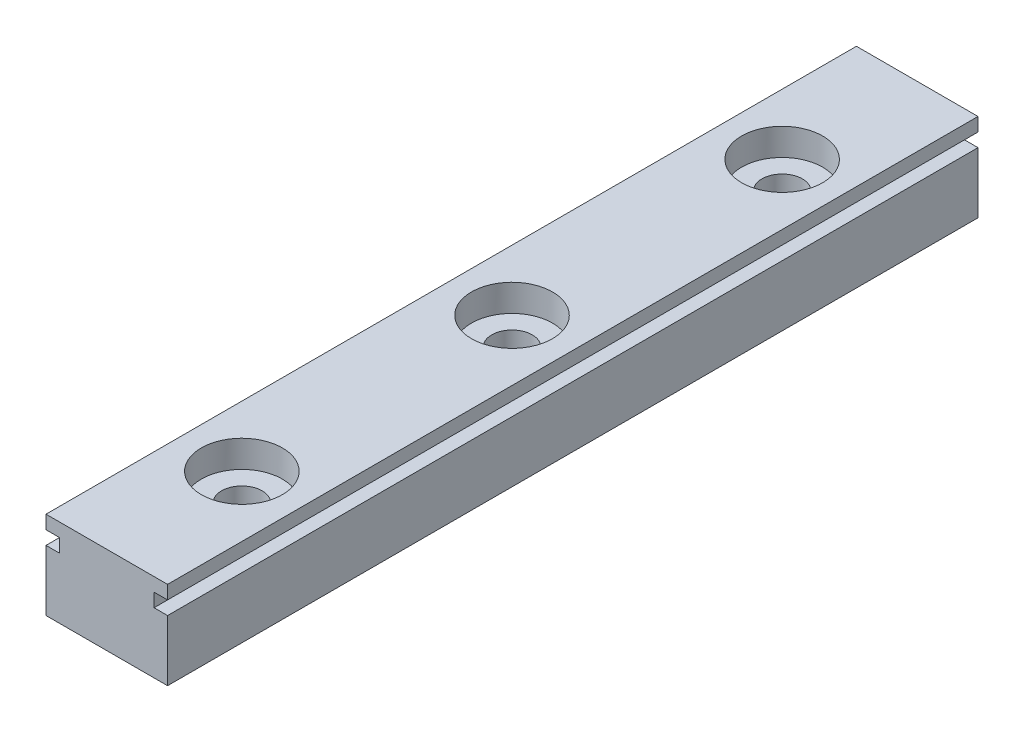
SolidWorks part; units mm, degrees
ref_plane "前视基准面" through (0, 0, 0) normal (0, 0, 1) x (1, 0, 0)
ref_plane "上视基准面" through (0, 0, 0) normal (0, 1, 0) x (1, 0, 0)
ref_plane "右视基准面" through (0, 0, 0) normal (1, 0, 0) x (0, 0, -1)
sketch "Sketch1" plane through (0, 0, 0) normal (0, 0, 1) x (1, 0, 0)
  line L0 (0, 0) -> (0, 6.7941) construction
  line L1 (4.5, 6.5) -> (-4.5, 6.5)
  line L2 (-4.5, 6.5) -> (-4.5, 5.5)
  line L3 (-4.5, 5.5) -> (-3.5, 5.5)
  line L4 (-3.5, 5.5) -> (-3.5, 4.5)
  line L5 (-3.5, 4.5) -> (-4.5, 4.5)
  line L6 (-4.5, 4.5) -> (-4.5, 0)
  line L7 (-4.5, 0) -> (4.5, 0)
  line L8 (3.5, 4.5) -> (4.5, 4.5)
  line L9 (4.5, 4.5) -> (4.5, 0)
  line L10 (4.5, 6.5) -> (4.5, 5.5)
  line L11 (4.5, 5.5) -> (3.5, 5.5)
  line L12 (3.5, 5.5) -> (3.5, 4.5)
  point P17 (0, 6.5)
  dimension "D1" = 6.5
  dimension "D2" = 1
  dimension "D3" = 1
  dimension "D4" = 4.5
  dimension "D5" = 1
extrude "Extrude1" add sketch "Sketch1" along normal blind 60
sketch "Sketch2" plane through (0, 6.5, 0) normal (0, 1, 0) x (1, 0, 0)
  line L0 (4.5, 0) -> (-4.5, 0) construction
  circle A0 centre (0, -10) radius 3
  circle A36 centre (0, -30) radius 3
  circle A37 centre (0, -50) radius 3
  circle A38 centre (0, -70) radius 3
  circle A39 centre (0, -90) radius 3
  circle A40 centre (0, -110) radius 3
  circle A41 centre (0, -130) radius 3
  circle A42 centre (0, -150) radius 3
  circle A43 centre (0, -170) radius 3
  circle A44 centre (0, -190) radius 3
  circle A45 centre (0, -210) radius 3
  circle A46 centre (0, -230) radius 3
  circle A47 centre (0, -250) radius 3
  circle A48 centre (0, -270) radius 3
  circle A49 centre (0, -290) radius 3
  circle A50 centre (0, -310) radius 3
  circle A51 centre (0, -330) radius 3
  circle A52 centre (0, -350) radius 3
  circle A53 centre (0, -370) radius 3
  circle A54 centre (0, -390) radius 3
  circle A55 centre (0, -410) radius 3
  circle A56 centre (0, -430) radius 3
  circle A57 centre (0, -450) radius 3
  circle A58 centre (0, -470) radius 3
  circle A59 centre (0, -490) radius 3
  circle A60 centre (0, -510) radius 3
  circle A61 centre (0, -530) radius 3
  circle A62 centre (0, -550) radius 3
  circle A63 centre (0, -570) radius 3
  circle A64 centre (0, -590) radius 3
  circle A65 centre (0, -610) radius 3
  circle A66 centre (0, -630) radius 3
  dimension "D1" = 6
  dimension "D2" = 10
  dimension "D4" = 20
  dimension "D3" = 32
extrude "Extrude2" cut sketch "Sketch2" against normal up to surface (2 mm away) up to face at (4, 4.5, 30)
sketch "Sketch3" plane through (0, 4.5, 0) normal (0, 1, 0) x (1, 0, 0)
  circle A0 centre (0, -10) radius 1.5
  circle A1 centre (0, -30) radius 1.5
  circle A2 centre (0, -50) radius 1.5
  circle A3 centre (0, -70) radius 1.5
  circle A4 centre (0, -90) radius 1.5
  circle A5 centre (0, -110) radius 1.5
  circle A6 centre (0, -130) radius 1.5
  circle A7 centre (0, -150) radius 1.5
  circle A8 centre (0, -170) radius 1.5
  circle A9 centre (0, -190) radius 1.5
  circle A10 centre (0, -210) radius 1.5
  circle A11 centre (0, -230) radius 1.5
  circle A12 centre (0, -250) radius 1.5
  circle A13 centre (0, -270) radius 1.5
  circle A14 centre (0, -290) radius 1.5
  circle A15 centre (0, -310) radius 1.5
  circle A16 centre (0, -330) radius 1.5
  circle A17 centre (0, -350) radius 1.5
  circle A18 centre (0, -370) radius 1.5
  circle A19 centre (0, -390) radius 1.5
  circle A20 centre (0, -410) radius 1.5
  circle A21 centre (0, -430) radius 1.5
  circle A22 centre (0, -450) radius 1.5
  circle A23 centre (0, -470) radius 1.5
  circle A24 centre (0, -490) radius 1.5
  circle A25 centre (0, -510) radius 1.5
  circle A26 centre (0, -530) radius 1.5
  circle A27 centre (0, -550) radius 1.5
  circle A28 centre (0, -570) radius 1.5
  circle A29 centre (0, -590) radius 1.5
  circle A30 centre (0, -610) radius 1.5
  circle A31 centre (0, -630) radius 1.5
  dimension "D1" = 3
  dimension "D3" = 20
  dimension "D2" = 32
extrude "Extrude4" cut sketch "Sketch3" against normal through all
